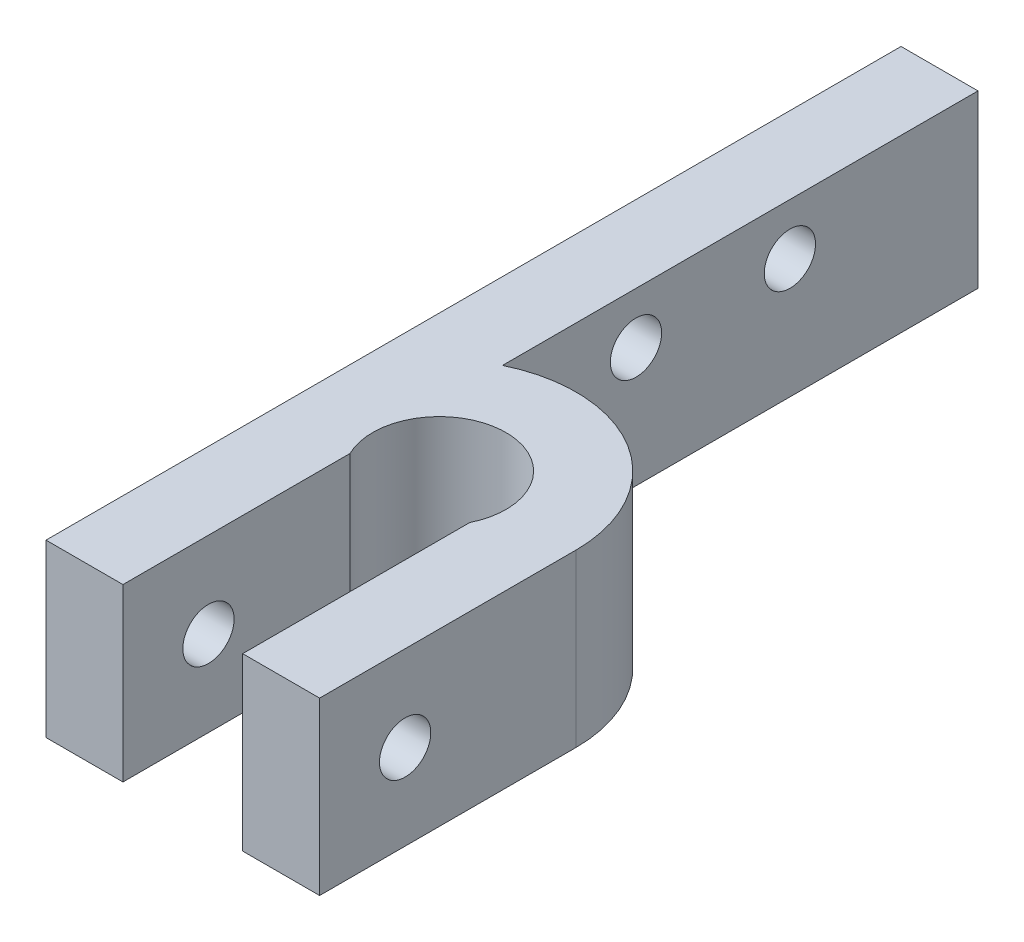
SolidWorks part; units mm, degrees
ref_plane "Front Plane" through (0, 0, 0) normal (0, 0, 1) x (1, 0, 0)
ref_plane "Top Plane" through (0, 0, 0) normal (0, 1, 0) x (1, 0, 0)
ref_plane "Right Plane" through (0, 0, 0) normal (1, 0, 0) x (0, 0, -1)
sketch "Sketch1" plane through (0, 0, 0) normal (0, 1, 0) x (1, 0, 0)
  line L0 (-8, -15) -> (-8, 35)
  line L1 (-8, 35) -> (-3.5, 35)
  line L2 (-3.5, 35) -> (-3.5, 7.1937)
  line L3 (-8, -15) -> (-3.5, -15)
  line L4 (-3.5, -15) -> (-3.5, -1.7205)
  line L5 (3.5, -1.7205) -> (3.5, -15)
  line L6 (3.5, -15) -> (8, -15)
  line L7 (8, -15) -> (8, 0)
  arc A0 (-3.5, 7.1937) -> (8, 0) centre (0, 0) cw
  arc A1 (-3.5, -1.7205) -> (3.5, -1.7205) centre (0, 0) cw
  dimension "D4" = 3.9
  dimension "D5" = 7
  dimension "D6" = 8
  dimension "D1" = 4.5
  dimension "D2" = 50
  dimension "D3" = 15
extrude "Boss-Extrude1" add sketch "Sketch1" along normal blind 10
sketch "Sketch2" plane through (-8, 0, 0) normal (-1, 0, 0) x (0, 0, 1)
  line L0 (-35, 0) -> (15, 0) construction
  line L1 (15, 10) -> (5, 10) construction
  line L2 (15, 10) -> (15, 0) construction
  line L3 (15, 0) -> (5, 0) construction
  line L4 (5, 10) -> (5, 0) construction
  line L5 (5, 10) -> (15, 0) construction
  line L6 (15, 10) -> (5, 0) construction
  circle A0 centre (10, 5) radius 1.5
  dimension "D1" = 3
extrude "Cut-Extrude1" cut sketch "Sketch2" against normal through all
sketch "Sketch3" plane through (-8, 0, 0) normal (-1, 0, 0) x (0, 0, 1)
  line L0 (-35, 7) -> (15, 7) construction
  line L1 (-35, 10) -> (-35, 0) construction
  line L2 (15, 10) -> (15, 0) construction
  line L3 (-35, 0) -> (15, 0) construction
  circle A0 centre (-24, 7) radius 1.5
  circle A1 centre (-15, 7) radius 1.5
  dimension "D2" = 3
  dimension "D1" = 7
  dimension "D3" = 11
  dimension "D4" = 9
extrude "Cut-Extrude2" cut sketch "Sketch3" against normal through all
